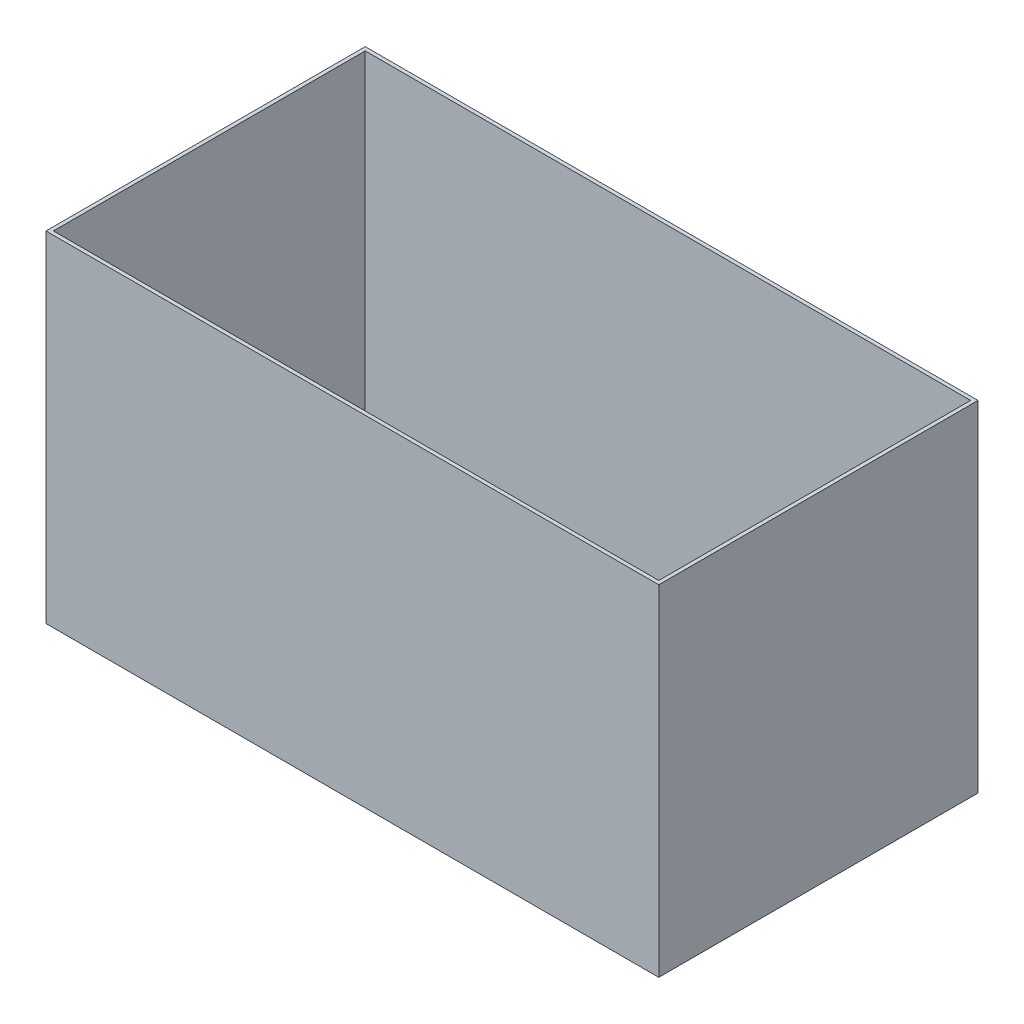
SolidWorks part; units mm, degrees
ref_plane "Front Plane" through (0, 0, 0) normal (0, 0, 1) x (1, 0, 0)
ref_plane "Top Plane" through (0, 0, 0) normal (0, 1, 0) x (1, 0, 0)
ref_plane "Right Plane" through (0, 0, 0) normal (1, 0, 0) x (0, 0, -1)
sketch "Sketch1" plane through (0, 0, 0) normal (0, 1, 0) x (1, 0, 0)
  line L1 (-231.3186, 43.1875) -> (758.6814, 43.1875)
  line L2 (-231.3186, 43.1875) -> (-231.3186, 553.1875)
  line L3 (-231.3186, 553.1875) -> (758.6814, 553.1875)
  line L4 (758.6814, 43.1875) -> (758.6814, 553.1875)
extrude "Boss-Extrude3" add sketch "Sketch1" along normal blind 550
shell "Shell4" thickness 6
